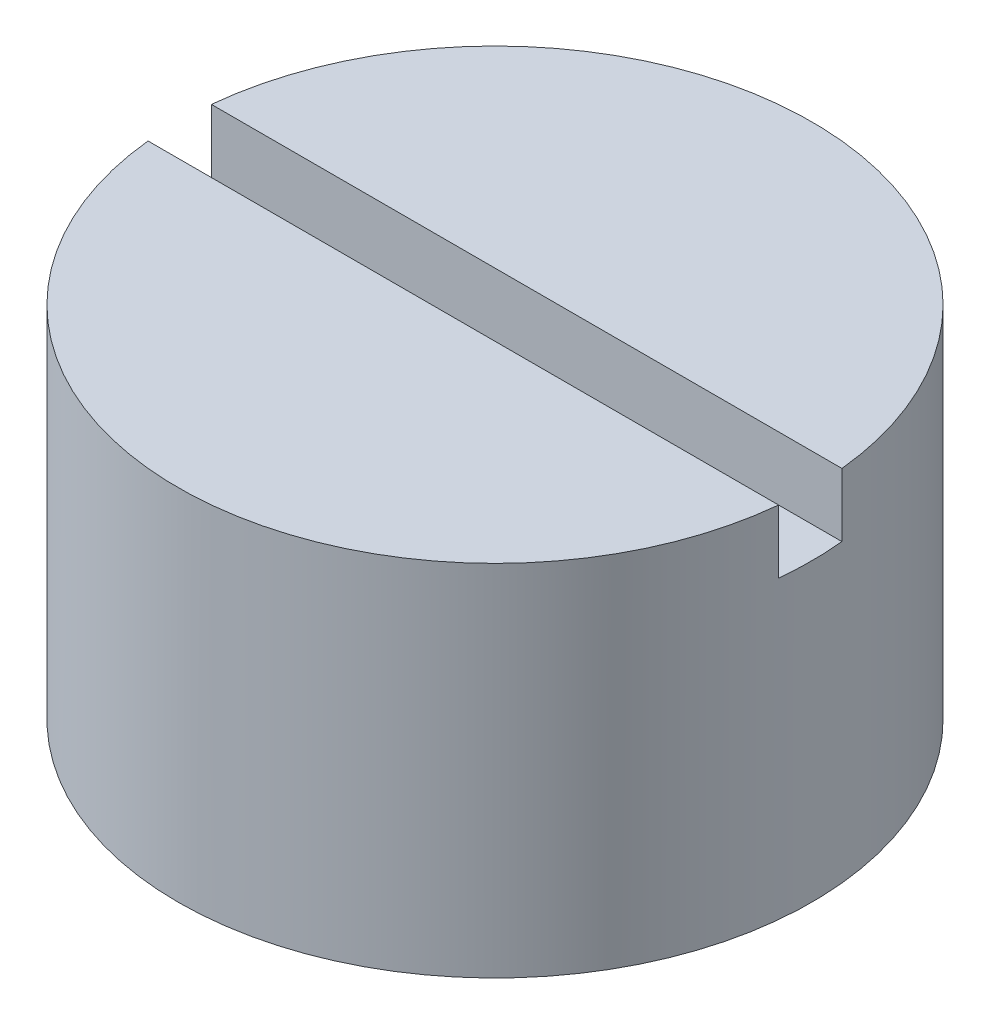
SolidWorks part; units mm, degrees
ref_plane "Front Plane" through (0, 0, 0) normal (0, 0, 1) x (1, 0, 0)
ref_plane "Top Plane" through (0, 0, 0) normal (0, 1, 0) x (1, 0, 0)
ref_plane "Right Plane" through (0, 0, 0) normal (1, 0, 0) x (0, 0, -1)
sketch "Sketch2" plane through (0, 0, 0) normal (0, 1, 0) x (1, 0, 0)
  line L1 (0, 12.846) -> (-11.125, 6.423)
  line L2 (-11.125, 6.423) -> (-11.125, -6.423)
  line L3 (-11.125, -6.423) -> (0, -12.846)
  line L4 (0, -12.846) -> (11.125, -6.423)
  line L5 (11.125, -6.423) -> (11.125, 6.423)
  line L6 (11.125, 6.423) -> (0, 12.846)
  circle A0 centre (0, 0) radius 11.125 construction
  circle A1 centre (0, 0) radius 15
  dimension "D2" = 30
  dimension "D1" = 22.25
extrude "Boss-Extrude1" add sketch "Sketch2" along normal mid plane 12
sketch "Sketch3" plane through (0, 6, 0) normal (0, 1, 0) x (1, 0, 0)
  circle A1 centre (0, 0) radius 15
  circle A2 centre (0, 0) radius 15
  dimension "D1" = 0
extrude "Boss-Extrude2" add sketch "Sketch3" along normal blind 5
sketch "Sketch4" plane through (0, 11, 0) normal (0, 1, 0) x (1, 0, 0)
  line L1 (16, -1.5) -> (-16, -1.5)
  line L2 (16, -1.5) -> (16, 1.5)
  line L3 (16, 1.5) -> (-16, 1.5)
  line L4 (-16, -1.5) -> (-16, 1.5)
  line L5 (16, -1.5) -> (-16, 1.5) construction
  line L6 (16, 1.5) -> (-16, -1.5) construction
  point P0 (0, 0)
  dimension "D1" = 3
  dimension "D2" = 32
extrude "Cut-Extrude1" cut sketch "Sketch4" against normal blind 3
